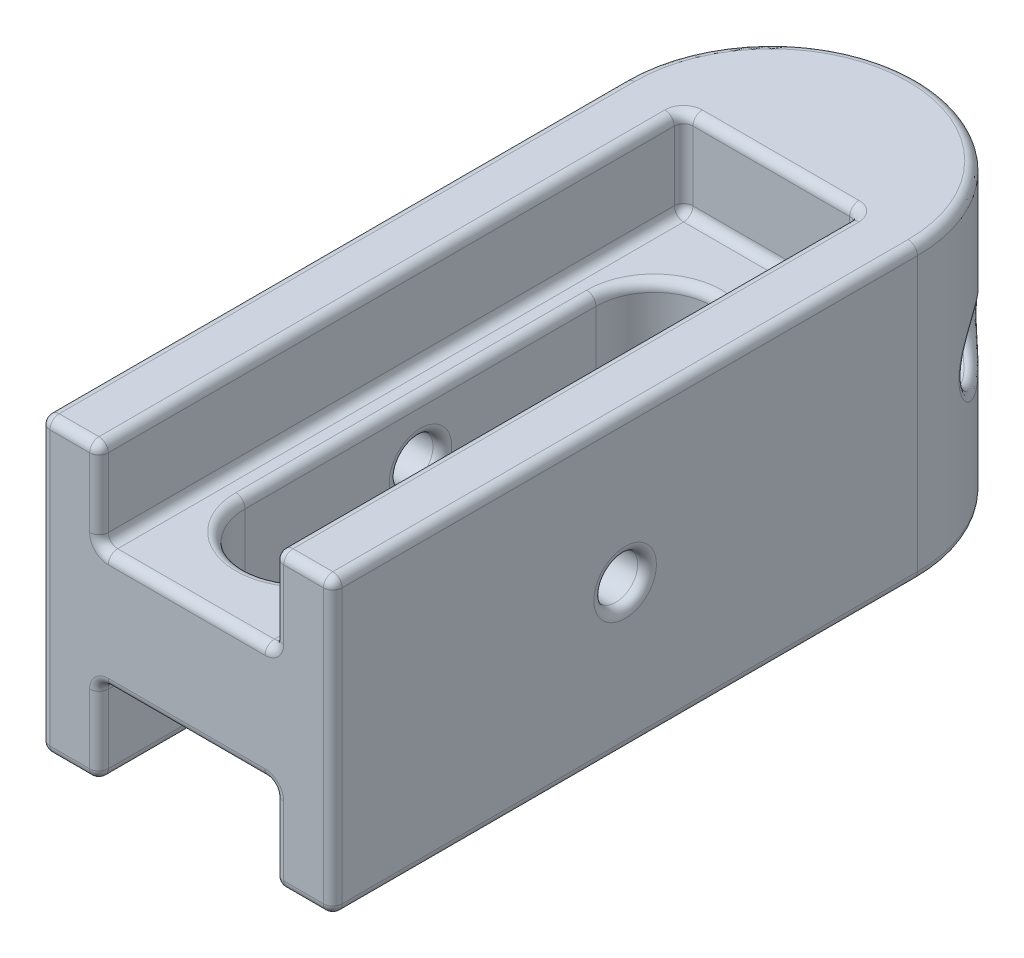
SolidWorks part; units mm, degrees
material "PET"
ref_plane "Front Plane" through (0, 0, 0) normal (0, 0, 1) x (1, 0, 0)
ref_plane "Top Plane" through (0, 0, 0) normal (0, 1, 0) x (1, 0, 0)
ref_plane "Right Plane" through (0, 0, 0) normal (1, 0, 0) x (0, 0, -1)
sketch "Sketch1" plane through (0, 0, 0) normal (0, 0, 1) x (1, 0, 0)
  line L1 (-9.525, 9.525) -> (9.525, 9.525) construction
  line L2 (-9.525, 9.525) -> (-9.525, -9.525) construction
  line L3 (-9.525, -9.525) -> (9.525, -9.525) construction
  line L4 (9.525, 9.525) -> (9.525, -9.525) construction
  line L5 (-9.525, 9.525) -> (9.525, -9.525) construction
  line L6 (-9.525, -9.525) -> (9.525, 9.525) construction
  line L7 (-7.9375, 7.9375) -> (7.9375, 7.9375)
  line L8 (-7.9375, 7.9375) -> (-7.9375, -7.9375)
  line L9 (-7.9375, -7.9375) -> (7.9375, -7.9375)
  line L10 (7.9375, 7.9375) -> (7.9375, -7.9375)
  line L11 (-7.9375, 7.9375) -> (7.9375, -7.9375) construction
  line L12 (-7.9375, -7.9375) -> (7.9375, 7.9375) construction
  point P0 (0, 0)
  point P6 (0, 0)
  dimension "D1" = 19.05
  dimension "D2" = 19.05
  dimension "D3" = 1.5875
extrude "Boss-Extrude1" add sketch "Sketch1" along normal blind 31.75
ref_plane "Plane1" through (0, 0, 0) normal (0, 1, 0) x (1, 0, 0)
sketch "Sketch3" plane through (0, 0, 0) normal (0, 1, 0) x (1, 0, 0)
  line L0 (7.9375, 0) -> (-7.9375, 0) construction
  line L1 (-7.9375, 0) -> (7.9375, 0)
  arc A0 (-7.9375, 0) -> (7.9375, 0) centre (0, 0) cw
extrude "Boss-Extrude3" add sketch "Sketch3" along normal blind 3.175 and the other way blind 3.175
sketch "Sketch4" plane through (7.9375, 0, 0) normal (1, 0, 0) x (0, 0, -1)
  line L0 (-31.75, 0) -> (0, 0) construction
  line L1 (-31.75, -7.9375) -> (-31.75, 7.9375) construction
  line L2 (-15.875, 7.9375) -> (-15.875, -7.9375) construction
  line L3 (-31.75, 7.9375) -> (0, 7.9375) construction
  line L4 (-31.75, -7.9375) -> (0, -7.9375) construction
  line L5 (-31.75, 0) -> (0, 0) construction
  circle A0 centre (-15.875, 0) radius 1.1906
  dimension "D1" = 2.3813
extrude "Cut-Extrude1" cut sketch "Sketch4" against normal through all
sketch "Sketch5" plane through (0, 0, 0) normal (0, 1, 0) x (1, 0, 0)
  line L0 (0, 0) -> (-4.7214, 6.3806)
  line L1 (0, 0) -> (6.3806, 4.7214)
  line L2 (-7.9375, 0) -> (7.9375, 0) construction
  arc A0 (7.9375, 0) -> (-7.9375, 0) centre (0, 0) ccw construction
  dimension "D1" = 53.5
ref_plane "Plane2" through (-4.7214, 0, -6.3806) normal (0.5948, 0, 0.8039) x (0.8039, 0, -0.5948)
sketch "Sketch7" plane through (-4.7214, 0, -6.3806) normal (0.5948, 0, 0.8039) x (0.8039, 0, -0.5948)
  circle A0 centre (0, 0) radius 1.5875
  dimension "D1" = 3.175
ref_plane "Plane3" through (6.3806, 0, -4.7214) normal (0.8039, 0, -0.5948) x (-0.5948, 0, -0.8039)
sketch "Sketch8" plane through (6.3806, 0, -4.7214) normal (0.8039, 0, -0.5948) x (-0.5948, 0, -0.8039)
  circle A0 centre (0, 0) radius 1.5875
  dimension "D1" = 3.175
extrude "Cut-Extrude3" cut sketch "Sketch8" against normal up to vertex (7.9375 mm away) contours A0 up to point (0, 0, 0)
extrude "Cut-Extrude4" cut sketch "Sketch7" along normal up to vertex (6.35 mm away) contours A0
sketch "Sketch9" plane through (0, 0, 0) normal (0, 0, -1) x (-1, 0, 0)
  line L0 (-7.9375, 7.9375) -> (7.9375, 7.9375) construction
  line L1 (-4.7625, 7.9375) -> (4.7625, 7.9375)
  line L2 (-4.7625, 7.9375) -> (-4.7625, 3.175)
  line L3 (-4.7625, 3.175) -> (4.7625, 3.175)
  line L4 (4.7625, 7.9375) -> (4.7625, 3.175)
  line L5 (7.9375, 3.175) -> (-7.9375, 3.175) construction
  line L6 (-7.9375, 3.175) -> (-7.9375, 7.9375) construction
  line L7 (7.9375, 7.9375) -> (7.9375, 3.175) construction
  line L8 (-7.9375, 0) -> (7.9375, 0) construction
  line L9 (-7.9375, -3.175) -> (-7.9375, 3.175) construction
  line L10 (7.9375, -3.175) -> (7.9375, 3.175) construction
  line L11 (-4.7625, -7.9375) -> (4.7625, -7.9375)
  line L12 (-4.7625, -3.175) -> (4.7625, -3.175)
  line L13 (4.7625, -7.9375) -> (4.7625, -3.175)
  line L14 (-4.7625, -7.9375) -> (-4.7625, -3.175)
  dimension "D1" = 3.175
  dimension "D2" = 3.175
extrude "Cut-Extrude5" cut sketch "Sketch9" against normal through all
sketch "Sketch10" plane through (0, -3.175, 0) normal (0, -1, 0) x (-1, 0, 0)
  line L0 (0, -31.75) -> (0, 0) construction
  line L1 (4.7625, -31.75) -> (-4.7625, -31.75) construction
  line L2 (0, -25.4) -> (0, -6.35) construction
  line L3 (-3.175, -25.4) -> (-3.175, -6.35)
  line L4 (3.175, -25.4) -> (3.175, -6.35)
  arc A0 (-3.175, -25.4) -> (3.175, -25.4) centre (0, -25.4) ccw
  arc A1 (3.175, -6.35) -> (-3.175, -6.35) centre (0, -6.35) ccw
  point P7 (0, -15.875)
  dimension "D1" = 6.35
  dimension "D2" = 6.35
extrude "Cut-Extrude6" cut sketch "Sketch10" against normal through all
fillet "Fillet1" radius 0.508 2 edges at (7.181, -0.33, -3.3819) (-3.3819, 0.33, -7.181)
fillet "Fillet14" radius 0.508 4 edges at (3.175, 0, 14.6844) (7.9375, 0, 14.6844) (-3.175, 0, 17.0656) (-7.9375, 0, 14.6844)
sketch "Sketch13" plane through (0, 3.175, 0) normal (0, 1, 0) x (1, 0, 0)
  line L0 (-7.9375, 0) -> (7.9375, 0)
  arc A0 (7.9375, 0) -> (-7.9375, 0) centre (0, 0) ccw
extrude "Boss-Extrude14" add sketch "Sketch13" along normal blind 4.7625
mirror "Mirror1" about plane through (0, 0, 0) normal (0, 1, 0) of "Boss-Extrude14"
fillet "Fillet15" radius 0.508 42 edges at (-7.9375, 0, 31.75) (0, 3.175, 0) (0, 7.9375, -7.9375) (0, 7.9375, 0) (-6.35, -7.9375, 31.75) (0, -7.9375, 0) (0, -7.9375, -7.9375) (0, -3.175, 0) (7.9375, 0, 31.75) (-6.35, 7.9375, 31.75) (4.7625, 5.5563, 31.75) (4.7625, 3.175, 15.875) (4.7625, 7.9375, 15.875) (-4.7625, 5.5563, 31.75) (-4.7625, 7.9375, 15.875) (0, 3.175, 31.75) (-4.7625, 3.175, 15.875) (4.7625, 5.5563, 0) (-4.7625, 5.5563, 0) (6.35, -7.9375, 31.75) (4.7625, -5.5563, 31.75) (4.7625, -7.9375, 15.875) (0, -3.175, 31.75) (4.7625, -3.175, 15.875) (-4.7625, -5.5563, 31.75) (-4.7625, -3.175, 15.875) (-4.7625, -7.9375, 15.875) (4.7625, -5.5563, 0) (-4.7625, -5.5563, 0) (6.35, 7.9375, 31.75) (7.9375, -7.9375, 15.875) (-7.9375, -7.9375, 15.875) (-7.9375, 7.9375, 15.875) (7.9375, 7.9375, 15.875) (0, 3.175, 3.175) (0, 3.175, 28.575) (3.175, 3.175, 15.875) (-3.175, 3.175, 15.875) (0, -3.175, 28.575) (-3.175, -3.175, 15.875) (0, -3.175, 3.175) (3.175, -3.175, 15.875)
sketch "Sketch14" plane through (0, 0, 0) normal (0, 1, 0) x (1, 0, 0)
  line L0 (0.3326, 2.2253) -> (-2.4679, 0.153)
  line L1 (-2.4679, 0.153) -> (-0.2983, -2.7789)
  line L2 (-0.2983, -2.7789) -> (2.5022, -0.7066)
  line L3 (2.5022, -0.7066) -> (0.3326, 2.2253)
  line L4 (0, 0) -> (-4.7214, 6.3806) construction
  point P6 (0.3262, 2.2377)
  point P7 (-0.2983, -2.7789)
  point P8 (0.3326, 2.2253)
extrude "Boss-Extrude15" add sketch "Sketch14" along normal mid plane 5.08
equation "\"0..015in\"=0.625"
